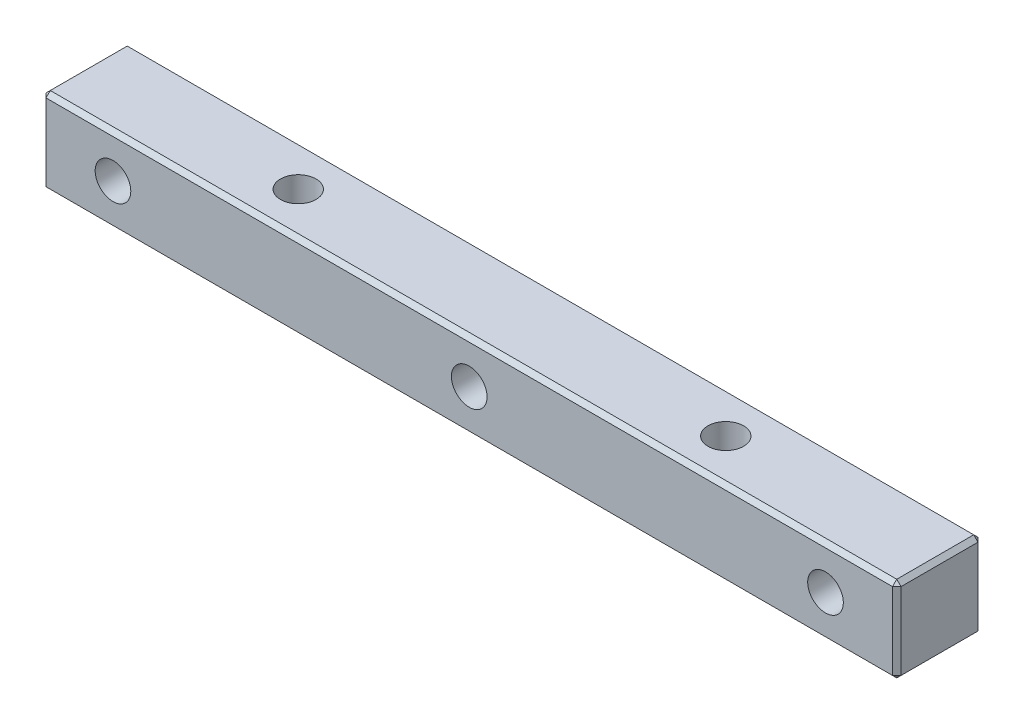
SolidWorks part; units mm, degrees
material "6061 合金"
ref_plane "前视基准面" through (0, 0, 0) normal (0, 0, 1) x (1, 0, 0)
ref_plane "上视基准面" through (0, 0, 0) normal (0, 1, 0) x (1, 0, 0)
ref_plane "右视基准面" through (0, 0, 0) normal (1, 0, 0) x (0, 0, -1)
other "Configuration Table"
sketch "草图1" plane through (0, 0, 0) normal (0, 0, 1) x (1, 0, 0)
  line L1 (-30, -3) -> (30, -3)
  line L2 (-30, -3) -> (-30, 3)
  line L3 (-30, 3) -> (30, 3)
  line L4 (30, -3) -> (30, 3)
  line L5 (-30, -3) -> (30, 3) construction
  line L6 (-30, 3) -> (30, -3) construction
  point P0 (0, 0)
  dimension "D1" = 60
  dimension "D2" = 6
extrude "凸台-拉伸1" add sketch "草图1" along normal mid plane 6
sketch "草图2" plane through (0, 0, 3) normal (0, 0, 1) x (1, 0, 0)
  line L0 (-25, 0) -> (25, 0) construction
  circle A0 centre (-25, 0) radius 1.25
  circle A1 centre (0, 0) radius 1.25
  circle A2 centre (25, 0) radius 1.25
  point P4 (0, 0)
  dimension "D2" = 2.5
  dimension "D1" = 50
sketch "草图3" plane through (0, 3, 0) normal (0, 1, 0) x (1, 0, 0)
  line L0 (-15, 0) -> (15, 0) construction
  point P4 (0, 0)
  dimension "D1" = 30
hole_wizard "M3 螺纹孔1" positions "草图4" profile "草图5" tap size "M3" standard "GB" end condition through all
sketch "草图4" plane through (0, 0, 3) normal (0, 0, 1) x (1, 0, 0)
  point P0 (-25, 0)
  point P3 (0, 0)
  point P6 (25, 0)
sketch "草图5" plane through (-25, 0, 3) normal (1, 0, 0) x (0, -1, 0)
  line L0 (0, 0) -> (0, 6)
  line L1 (0, 6) -> (1.25, 6)
  line L2 (1.25, 6) -> (1.25, 0)
  line L5 (1.25, 0) -> (0, 0)
  line L11 (0, -6.35) -> (0, 107.95) construction
  dimension "通孔螺纹孔钻头直径" = 2.5
  dimension "通孔螺纹孔钻头深度" = 6
cosmetic thread "孔螺蚊线1" parameters "D2"=3
cosmetic thread "孔螺蚊线2" parameters "D2"=3
cosmetic thread "孔螺蚊线3" parameters "D2"=3
hole_wizard "M3 螺纹孔2" positions "草图6" profile "草图7" tap size "M3" standard "GB" end condition through all
sketch "草图6" plane through (0, 3, 0) normal (0, 1, 0) x (1, 0, 0)
  point P0 (-15, 0)
  point P3 (15, 0)
sketch "草图7" plane through (-15, 3, 0) normal (1, 0, 0) x (0, 0, 1)
  line L0 (0, 0) -> (0, 6)
  line L1 (0, 6) -> (1.25, 6)
  line L2 (1.25, 6) -> (1.25, 0)
  line L5 (1.25, 0) -> (0, 0)
  line L11 (0, -6.35) -> (0, 107.95) construction
  dimension "通孔螺纹孔钻头直径" = 2.5
  dimension "通孔螺纹孔钻头深度" = 6
cosmetic thread "孔螺蚊线4" parameters "D2"=3
cosmetic thread "孔螺蚊线5" parameters "D2"=3
chamfer "倒角1" distance 0.3 angle 45 12 edges at (-30, 3, 0) (-30, 0, 3) (-30, -3, 0) (-30, 0, -3) (30, 0, 3) (0, -3, 3) (30, -3, 0) (0, -3, -3) (30, 0, -3) (0, 3, -3) (30, 3, 0) (0, 3, 3)
